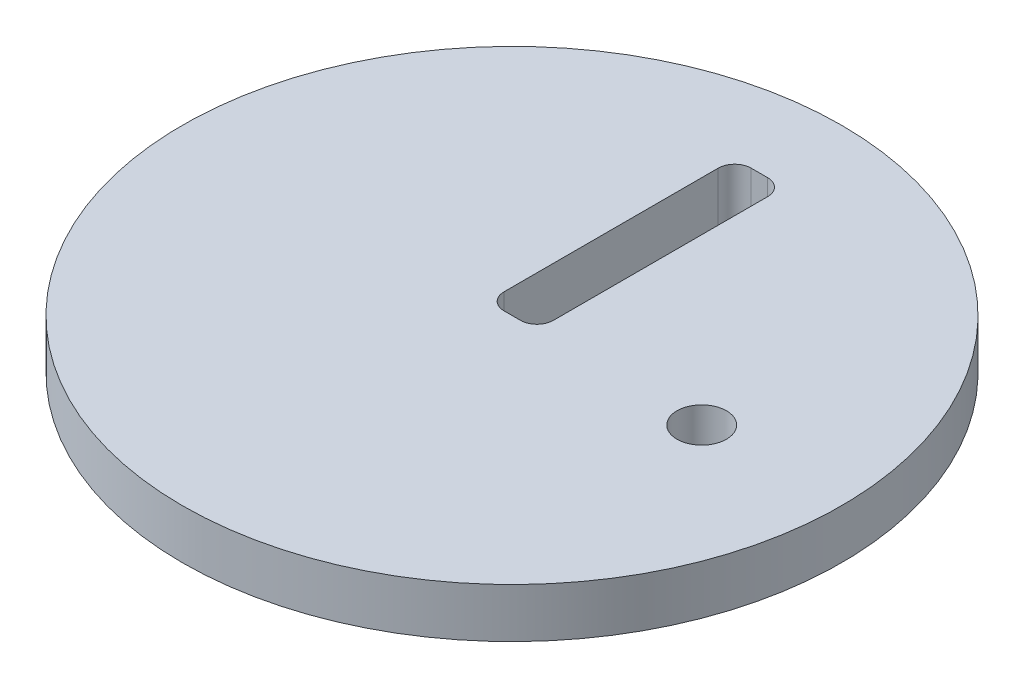
SolidWorks part; units mm, degrees
ref_plane "Front Plane" through (0, 0, 0) normal (0, 0, 1) x (1, 0, 0)
ref_plane "Top Plane" through (0, 0, 0) normal (0, 1, 0) x (1, 0, 0)
ref_plane "Right Plane" through (0, 0, 0) normal (1, 0, 0) x (0, 0, -1)
sketch "Sketch1" plane through (0, 0, 0) normal (0, 1, 0) x (1, 0, 0)
  circle A0 centre (0, 0) radius 20
  dimension "D1" = 40
extrude "Boss-Extrude1" add sketch "Sketch1" along normal blind 3
sketch "Sketch2" plane through (0, 3, 0) normal (0, 1, 0) x (1, 0, 0)
  line L1 (-1.4861, 15) -> (1.5139, 15)
  line L2 (-1.4861, 15) -> (-1.4861, 0)
  line L3 (-1.4861, 0) -> (1.5139, 0)
  line L4 (1.5139, 15) -> (1.5139, 0)
  line L5 (-1.4861, 15) -> (1.5139, 0) construction
  line L6 (-1.4861, 0) -> (1.5139, 15) construction
  point P0 (0.0139, 7.5)
  dimension "D1" = 15
  dimension "D2" = 3
extrude "Cut-Extrude1" cut sketch "Sketch2" against normal blind 3
sketch "Sketch3" plane through (0, 3, 0) normal (0, 1, 0) x (1, 0, 0)
  circle A0 centre (11.5139, 0) radius 1.5
  dimension "D1" = 3
  dimension "D2" = 10
extrude "Cut-Extrude2" cut sketch "Sketch3" against normal blind 3
fillet "Fillet1" radius 1 1 edges at (-1.4861, 1.5, -15)
fillet "Fillet2" radius 1 1 edges at (1.5139, 1.5, -15)
fillet "Fillet3" radius 1 1 edges at (-1.4861, 1.5, 0)
fillet "Fillet4" radius 1 1 edges at (1.5139, 1.5, 0)
